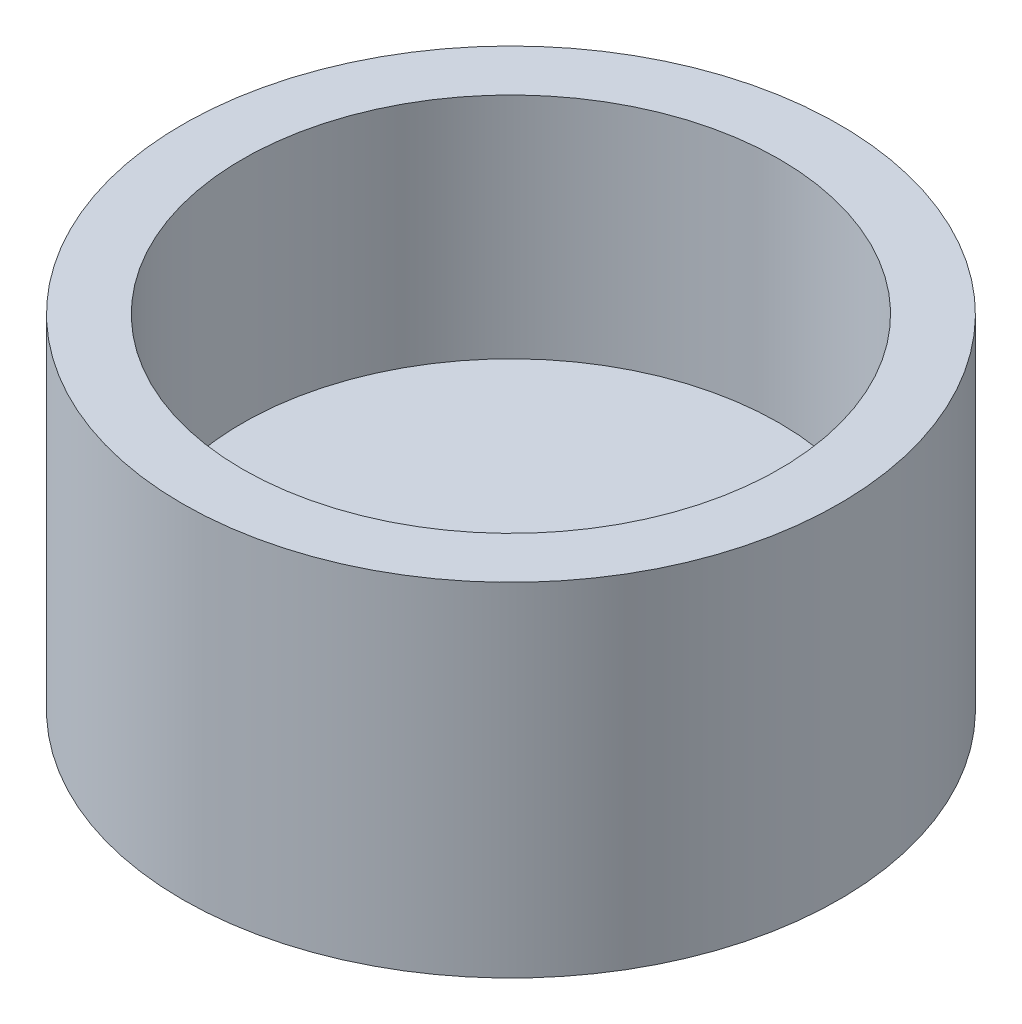
SolidWorks part; units mm, degrees
ref_plane "Front Plane" through (0, 0, 0) normal (0, 0, 1) x (1, 0, 0)
ref_plane "Top Plane" through (0, 0, 0) normal (0, 1, 0) x (1, 0, 0)
ref_plane "Right Plane" through (0, 0, 0) normal (1, 0, 0) x (0, 0, -1)
sketch "Sketch1" plane through (0, 0, 0) normal (0, 1, 0) x (1, 0, 0)
  circle A0 centre (0, 0) radius 5.75
  dimension "D1" = 11.5
extrude "Boss-Extrude1" add sketch "Sketch1" along normal blind 6 contours A0
sketch "Sketch2" plane through (0, 6, 0) normal (0, 1, 0) x (1, 0, 0)
  circle A0 centre (0, 0) radius 4.7
  dimension "D1" = 9.4
extrude "Cut-Extrude1" cut sketch "Sketch2" against normal blind 4 contours A0
